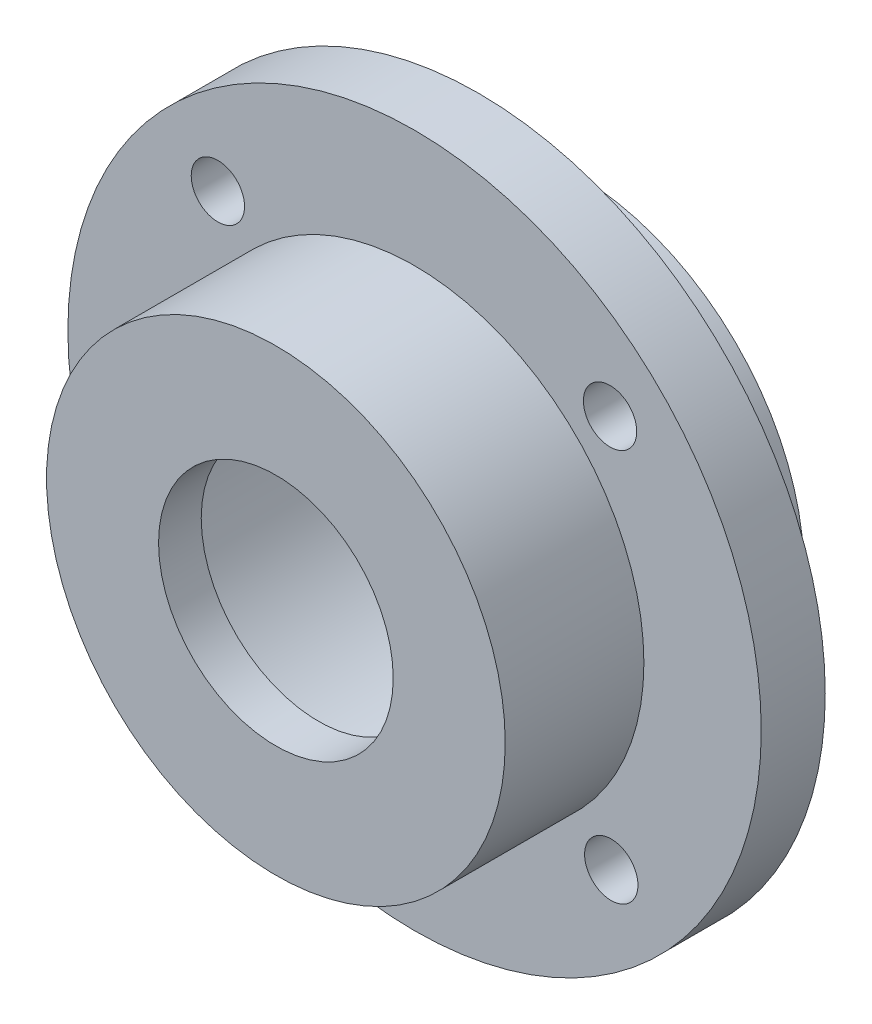
SolidWorks part; units mm, degrees
ref_plane "Спереди" through (0, 0, 0) normal (0, 0, 1) x (1, 0, 0)
ref_plane "Сверху" through (0, 0, 0) normal (0, 1, 0) x (1, 0, 0)
ref_plane "Справа" through (0, 0, 0) normal (1, 0, 0) x (0, 0, -1)
sketch "Эскиз1" plane through (0, 0, 0) normal (0, 0, 1) x (1, 0, 0)
  circle A0 centre (0, 0) radius 17.5
  circle A1 centre (0, 0) radius 32.5
  circle A2 centre (-18.4388, 18.3277) radius 2.5
  circle A3 centre (18.3277, 18.4388) radius 2.5
  circle A4 centre (18.4388, -18.3277) radius 2.5
  circle A5 centre (-18.3277, -18.4388) radius 2.5
  dimension "D1" = 5
  dimension "D2" = 35
  dimension "D3" = 65
  dimension "D4" = 5
  dimension "D5" = 5
  dimension "D6" = 5
extrude "Вытянуть1" add sketch "Эскиз1" along normal blind 24
sketch "Эскиз2" plane through (0, 0, 24) normal (0, 0, 1) x (1, 0, 0)
  circle A0 centre (0, 0) radius 21.5
  circle A1 centre (0, 0) radius 35
  dimension "D1" = 43
  dimension "D2" = 70
extrude "Вытянуть2" cut sketch "Эскиз2" against normal blind 9
sketch "Эскиз3" plane through (0, 0, 0) normal (0, 0, -1) x (-1, 0, 0)
  circle A0 centre (0, 0) radius 21.5
  circle A1 centre (0, 0) radius 35
  dimension "D1" = 43
  dimension "D2" = 70
extrude "Вытянуть3" cut sketch "Эскиз3" against normal blind 9
sketch "Эскиз4" plane through (0, 0, 24) normal (0, 0, 1) x (1, 0, 0)
  circle A2 centre (0, 0) radius 21.5
  circle A3 centre (0, 0) radius 11
  dimension "D1" = 22
  dimension "D2" = 43
extrude "Вытянуть4" add sketch "Эскиз4" along normal blind 4
